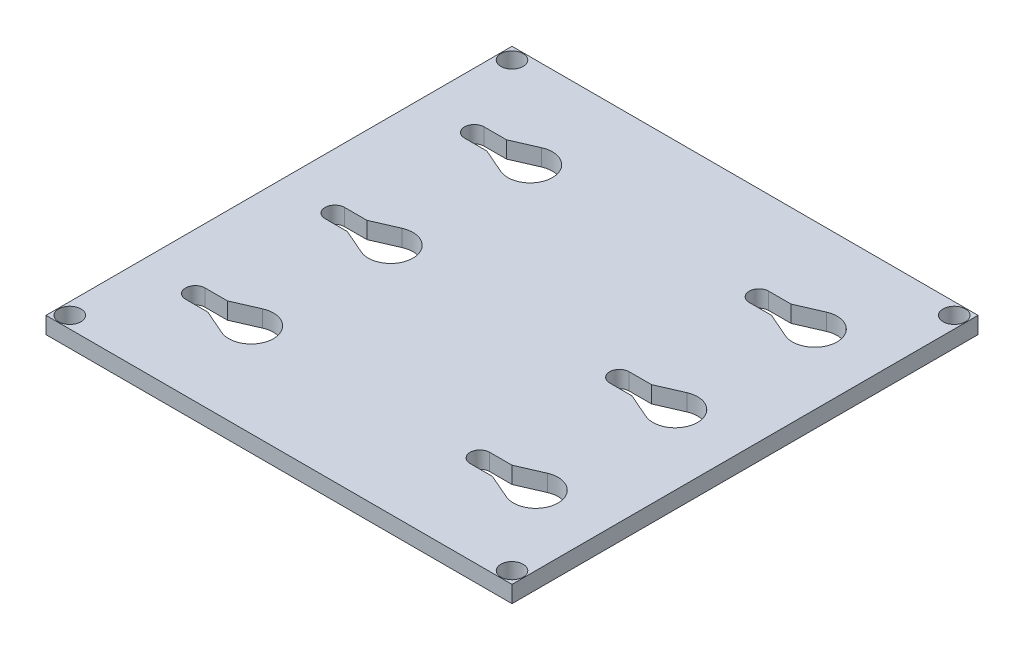
SolidWorks part; units mm, degrees
ref_plane "Piano frontale" through (0, 0, 0) normal (0, 0, 1) x (1, 0, 0)
ref_plane "Piano superiore" through (0, 0, 0) normal (0, 1, 0) x (1, 0, 0)
ref_plane "Piano destro" through (0, 0, 0) normal (1, 0, 0) x (0, 0, -1)
sketch "Schizzo1" plane through (0, 0, 0) normal (0, 1, 0) x (1, 0, 0)
  line L1 (41.75, -41.75) -> (-41.75, -41.75)
  line L2 (41.75, -41.75) -> (41.75, 41.75)
  line L3 (41.75, 41.75) -> (-41.75, 41.75)
  line L4 (-41.75, -41.75) -> (-41.75, 41.75)
  line L5 (41.75, -41.75) -> (-41.75, 41.75) construction
  line L6 (41.75, 41.75) -> (-41.75, -41.75) construction
  point P0 (0, 0)
  dimension "D1" = 83.5
extrude "Estrusione-Estrusione1" add sketch "Schizzo1" along normal blind 3
sketch "Schizzo2" plane through (0, 0, 0) normal (0, -1, 0) x (-1, 0, 0)
  circle A0 centre (39.6213, 39.6213) radius 2 construction
  circle A1 centre (39.6213, 39.6213) radius 2
  circle A2 centre (39.6213, -39.6213) radius 2 construction
  circle A3 centre (39.6213, -39.6213) radius 2
  circle A4 centre (-39.6213, 39.6213) radius 2 construction
  circle A5 centre (-39.6213, 39.6213) radius 2
  circle A6 centre (-39.6213, -39.6213) radius 2 construction
  circle A7 centre (-39.6213, -39.6213) radius 2
extrude "Taglio-Estrusione1" cut sketch "Schizzo2" against normal blind 3
sketch "Schizzo4" plane through (0, 0, 0) normal (0, -1, 0) x (1, 0, 0)
  line L0 (-31.75, 0) -> (-21.75, 0) construction
  line L1 (-41.75, -41.75) -> (-41.75, 41.75) construction
  line L2 (-31.75, -1.75) -> (-27.75, -1.75)
  line L3 (-27.75, -1.75) -> (-23.347, -3.6674)
  line L4 (-31.75, 1.75) -> (-27.75, 1.75)
  line L5 (-27.75, 1.75) -> (-23.347, 3.6674)
  circle A0 centre (-21.75, 0) radius 4
  circle A1 centre (-31.75, 0) radius 1.75
  point P14 (-22.9413, -3.8185)
  dimension "D1" = 3.5
  dimension "D2" = 8
  dimension "D3" = 10
  dimension "D4" = 10
  dimension "D5" = 4
extrude "Taglio-Estrusione2" cut sketch "Schizzo4" against normal through all
pattern_linear "Ripetizione a L1" count 2 spacing 51 along (1, 0, 0) count 2 spacing 25 along (0, 0, -1) of "Taglio-Estrusione2"
mirror "Specchia1" about plane through (0, 0, 0) normal (0, 0, 1) of "Ripetizione a L1"
